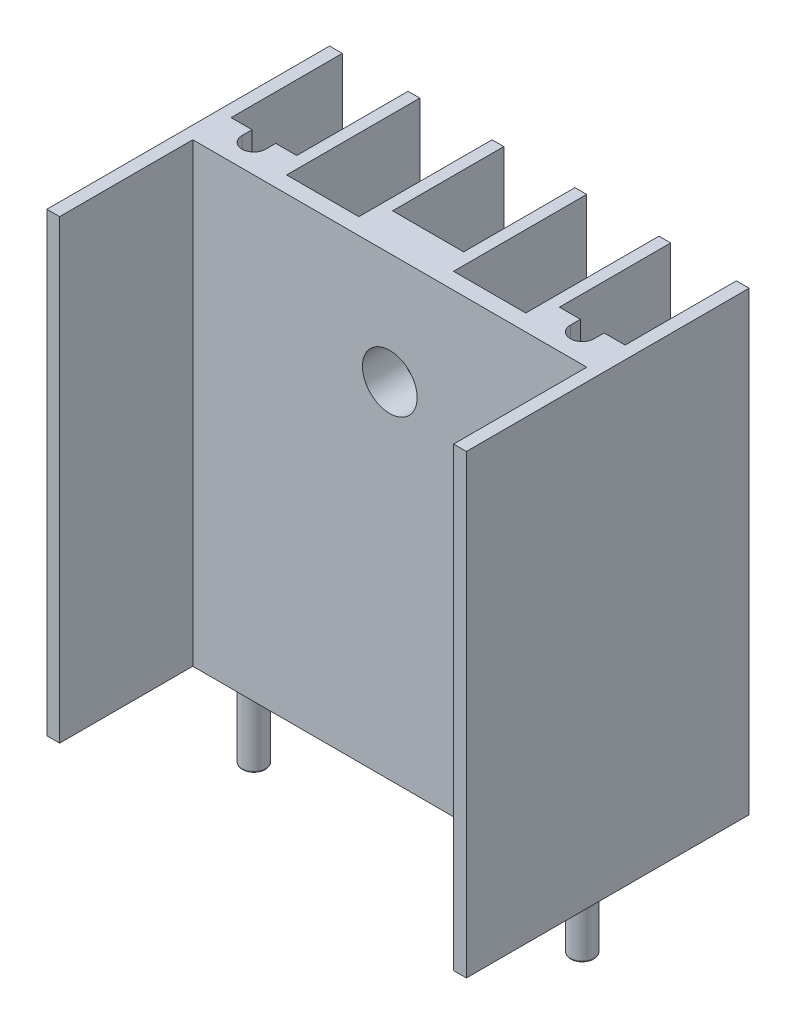
SolidWorks part; units mm, degrees
material "Alumina"
ref_plane "Front Plane" through (0, 0, 0) normal (0, 0, 1) x (1, 0, 0)
ref_plane "Top Plane" through (0, 0, 0) normal (0, 1, 0) x (1, 0, 0)
ref_plane "Right Plane" through (0, 0, 0) normal (1, 0, 0) x (0, 0, -1)
sketch "Sketch1" plane through (0, 0, 0) normal (0, 1, 0) x (1, 0, 0)
  line L1 (11.5, 7.75) -> (-11.5, 7.75)
  line L2 (11.5, 7.75) -> (11.5, -7.75)
  line L3 (11.5, -7.75) -> (-11.5, -7.75)
  line L4 (-11.5, 7.75) -> (-11.5, -7.75)
  line L5 (11.5, 7.75) -> (-11.5, -7.75) construction
  line L6 (11.5, -7.75) -> (-11.5, 7.75) construction
  point P0 (0, 0)
  dimension "D1" = 23
  dimension "D2" = 15.5
extrude "Height" add sketch "Sketch1" along normal blind 25
sketch "Sketch2" plane through (0, 25, 0) normal (0, 1, 0) x (1, 0, 0)
  line L0 (-11.5, 1.65) -> (-9.65, 1.65) construction
  line L1 (-11.5, 7.75) -> (-11.5, -7.75) construction
  line L2 (11.5, -7.75) -> (11.5, 7.75) construction
  line L3 (11.5, 7.75) -> (-11.5, 7.75) construction
  line L4 (-11.5, 0.45) -> (11.5, 0.45) construction
  line L5 (-1.95, 7.75) -> (1.95, 7.75)
  line L6 (-1.95, 7.75) -> (-1.95, 1.65)
  line L7 (-1.95, 1.65) -> (1.95, 1.65)
  line L8 (1.95, 7.75) -> (1.95, 1.65)
  line L9 (-10.8, 7.75) -> (-7.2, 7.75)
  line L10 (-10.8, 7.75) -> (-10.8, 1.65)
  line L11 (-10.8, 1.65) -> (-9.65, 1.65)
  line L12 (-7.2, 7.75) -> (-7.2, 1.65)
  line L13 (10.8, 7.75) -> (7.2, 7.75)
  line L14 (10.8, 7.75) -> (10.8, 1.65)
  line L15 (10.8, 1.65) -> (9.65, 1.65)
  line L16 (7.2, 7.75) -> (7.2, 1.65)
  line L17 (-7.2, 7.75) -> (-6.556, 7.75) construction
  line L18 (-6.556, 7.75) -> (-2.594, 7.75)
  line L19 (-6.556, 7.75) -> (-6.556, 0.45)
  line L20 (-6.556, 0.45) -> (-2.594, 0.45)
  line L21 (-2.594, 7.75) -> (-2.594, 0.45)
  line L22 (2.594, 7.75) -> (6.556, 7.75)
  line L23 (2.594, 7.75) -> (2.594, 0.45)
  line L24 (2.594, 0.45) -> (6.556, 0.45)
  line L25 (6.556, 7.75) -> (6.556, 0.45)
  line L26 (-2.594, 7.75) -> (-1.95, 7.75) construction
  line L27 (1.95, 7.75) -> (2.594, 7.75) construction
  line L28 (6.556, 7.75) -> (7.2, 7.75) construction
  line L29 (-11.5, -0.45) -> (11.5, -0.45) construction
  line L30 (-11.5, -7.75) -> (11.5, -7.75) construction
  line L31 (-9.65, 1.1) -> (-9.65, 1.65)
  line L32 (-10.8, -7.75) -> (10.8, -7.75)
  line L33 (-10.8, -7.75) -> (-10.8, -0.45)
  line L34 (-10.8, -0.45) -> (10.8, -0.45)
  line L35 (10.8, -7.75) -> (10.8, -0.45)
  line L36 (-8.35, 1.1) -> (-8.35, 1.65)
  line L37 (8.35, 1.1) -> (8.35, 1.65)
  line L38 (9.65, 1.1) -> (9.65, 1.65)
  line L39 (9.65, 1.65) -> (11.5, 1.65) construction
  line L40 (8.35, 1.65) -> (7.2, 1.65)
  line L43 (-8.35, 1.65) -> (8.35, 1.65) construction
  line L44 (-8.35, 1.65) -> (-7.2, 1.65)
  arc A0 (-9.65, 1.1) -> (-8.35, 1.1) centre (-9, 1.1) ccw
  arc A1 (8.35, 1.1) -> (9.65, 1.1) centre (9, 1.1) ccw
  point P12 (0, 7.75)
  point P41 (0, -7.75)
  dimension "D9" = 1.3
  dimension "D1" = 6.1
  dimension "D2" = 3.9
  dimension "D3" = 3.6
  dimension "D4" = 0.7
  dimension "D5" = 0.7
  dimension "D6" = 7.3
  dimension "D7" = 7.3
  dimension "D8" = 0.7
extrude "Profile Cut" cut sketch "Sketch2" against normal through all
sketch "Sketch3" plane through (0, 0, 0) normal (0, -1, 0) x (1, 0, 0)
  circle A0 centre (-9, -1.1) radius 0.65
  circle A1 centre (9, -1.1) radius 0.65
extrude "Boss-Extrude2" add sketch "Sketch3" along normal blind 4.5 and the other way blind 7.3 separate body
fillet "Fillet1" radius 0.1 2 edges at (9, -4.5, -1.75) (9, 7.3, -1.75)
fillet "Fillet2" radius 0.1 2 edges at (-9, 7.3, -1.75) (-9, -4.5, -1.75)
sketch "Sketch4" plane through (0, 0, -1.65) normal (0, 0, -1) x (-1, 0, 0)
  line L0 (1.95, 25) -> (-1.95, 25) construction
  circle A0 centre (0, 18.9) radius 1.5
  dimension "D2" = 3
  dimension "D1" = 7.6
extrude "Cut-Extrude2" cut sketch "Sketch4" against normal through all
equation "\"width\"=23"
equation "\"D1@Sketch1\"=\"width\""
equation "\"depth\"=15.5"
equation "\"D2@Sketch1\"=\"depth\""
equation "\"he\"=25"
equation "\"D1@Height\" = \"he\""
